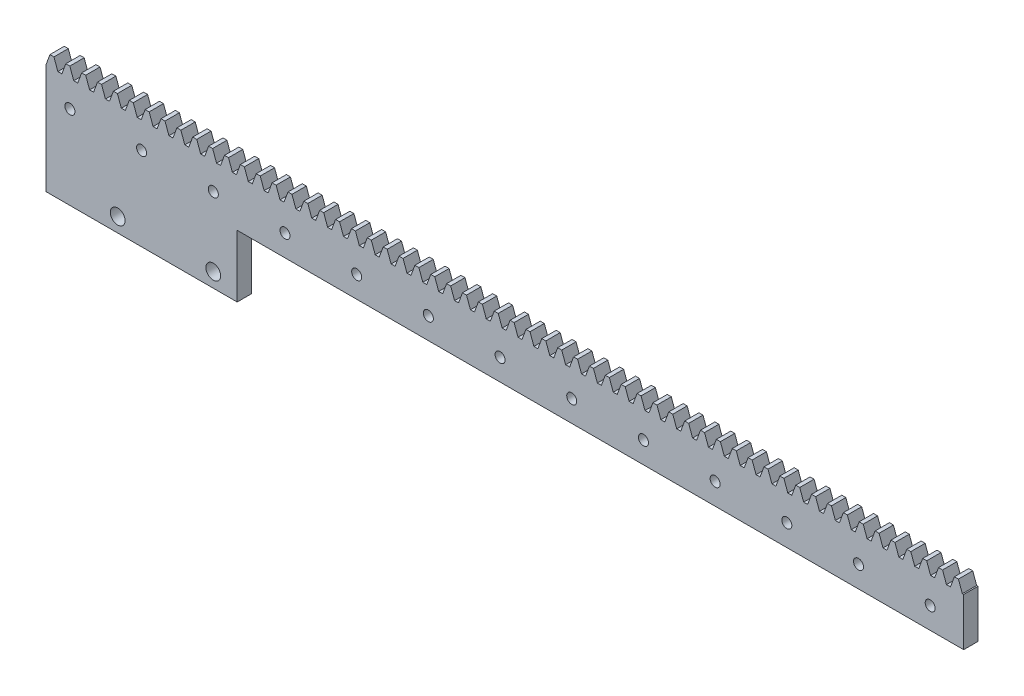
SolidWorks part; units mm, degrees
ref_plane "前视基准面" through (0, 0, 0) normal (0, 0, 1) x (1, 0, 0)
ref_plane "上视基准面" through (0, 0, 0) normal (0, 1, 0) x (1, 0, 0)
ref_plane "右视基准面" through (0, 0, 0) normal (1, 0, 0) x (0, 0, -1)
sketch "草图1" plane through (0, 0, 0) normal (0, 0, 1) x (1, 0, 0)
  line L1 (0, 0) -> (200, 0)
  line L2 (0, 0) -> (0, -10)
  line L3 (0, -10) -> (200, -10)
  line L4 (200, 0) -> (200, -10)
  dimension "D1" = 10
  dimension "L" = 200
extrude "拉伸1" add sketch "草图1" along normal blind 5
sketch "草图2" plane through (0, 0, 5) normal (0, 0, 1) x (1, 0, 0)
  line L0 (0, 0) -> (0.8189, 2.25)
  line L1 (0.8189, 2.25) -> (1.6618, 2.25)
  line L2 (1.6618, 2.25) -> (2.4807, 0)
  line L3 (200, 0) -> (0, 0) construction
  line L4 (0, 0) -> (2.4807, 0)
  line L5 (0.455, 1.25) -> (2.0258, 1.25) construction
  dimension "D2" = 70
  dimension "alpha" = 110
  dimension "ha" = 1
  dimension "hf" = 1.25
  dimension "S" = 1.5708
extrude "拉伸2" add sketch "草图2" against normal up to surface (5 mm away) up to face at (100, -5, 0)
pattern_linear "阵列(线性)1" count 60 spacing 3.32 along (1, 0, 0) of "拉伸2"
ref_plane "基准面1" through (0, 0, 0) normal (0, 0, -1) x (-1, 0, 0)
sketch "草图3" plane through (0, 0, 0) normal (0, 0, -1) x (-1, 0, 0)
  line L1 (-307.1129, 124.8102) -> (104.2543, 124.8102)
  line L2 (-307.1129, 124.8102) -> (-307.1129, -108.4491)
  line L3 (-307.1129, -108.4491) -> (104.2543, -108.4491)
  line L4 (104.2543, 124.8102) -> (104.2543, -108.4491)
extrude "切除-拉伸1" cut sketch "草图3" against normal blind 2
ref_plane "基准面2" through (0, 0, 5) normal (0, 0, 1) x (1, 0, 0)
sketch "草图4" plane through (0, 0, 5) normal (0, 0, 1) x (1, 0, 0)
  circle A0 centre (20, -5.5) radius 1.05
  circle A1 centre (35, -5.5) radius 1.05
  circle A2 centre (50, -5.5) radius 1.05
  circle A3 centre (65, -5.5) radius 1.05
  circle A4 centre (80, -5.5) radius 1.05
  circle A5 centre (95, -5.5) radius 1.05
  circle A6 centre (110, -5.5) radius 1.05
  circle A7 centre (125, -5.5) radius 1.05
  circle A8 centre (140, -5.5) radius 1.05
  circle A9 centre (155, -5.5) radius 1.05
  circle A10 centre (170, -5.5) radius 1.05
  circle A11 centre (185, -5.5) radius 1.05
  circle A12 centre (5, -5.5) radius 1.05
  dimension "D2" = 2.1
  dimension "D3" = 15
  dimension "D1" = 12
  dimension "D4" = 2
extrude "切除-拉伸2" cut sketch "草图4" against normal through all
sketch "草图5" plane through (0, 0, 5) normal (0, 0, 1) x (1, 0, 0)
  line L1 (0, -10) -> (40, -10)
  line L2 (0, -10) -> (0, -23)
  line L3 (0, -23) -> (40, -23)
  line L4 (40, -10) -> (40, -23)
  dimension "D1" = 13
  dimension "D2" = 40
extrude "凸台-拉伸1" add sketch "草图5" against normal through all
sketch "草图6" plane through (0, 0, 5) normal (0, 0, 1) x (1, 0, 0)
  line L0 (40, -20) -> (35, -20) construction
  line L2 (35, -20) -> (15, -20) construction
  line L3 (0, -23) -> (40, -23) construction
  line L4 (40, -23) -> (40, -10) construction
  circle A0 centre (35, -20) radius 1.55
  circle A1 centre (15, -20) radius 1.55
  dimension "D3" = 3.1
  dimension "D4" = 3.1
  dimension "D1" = 5
  dimension "D2" = 20
  dimension "D5" = 3
extrude "切除-拉伸3" cut sketch "草图6" against normal blind 10
ref_plane "基准面3" through (200, 0, 0) normal (1, 0, 0) x (0, 0, -1)
sketch "草图7" plane through (200, 0, 0) normal (1, 0, 0) x (0, 0, -1)
  line L1 (-33.7265, 29.1419) -> (10.9795, 29.1419)
  line L2 (-33.7265, 29.1419) -> (-33.7265, -24.1061)
  line L3 (-33.7265, -24.1061) -> (10.9795, -24.1061)
  line L4 (10.9795, 29.1419) -> (10.9795, -24.1061)
  line L5 (-33.7265, 29.1419) -> (10.9795, -24.1061) construction
  line L6 (-33.7265, -24.1061) -> (10.9795, 29.1419) construction
  point P0 (-11.3735, 2.5179)
extrude "切除-拉伸4" cut sketch "草图7" against normal blind 8
equation "\"D2@草图2\" = 180 - \"alpha@草图2\""
